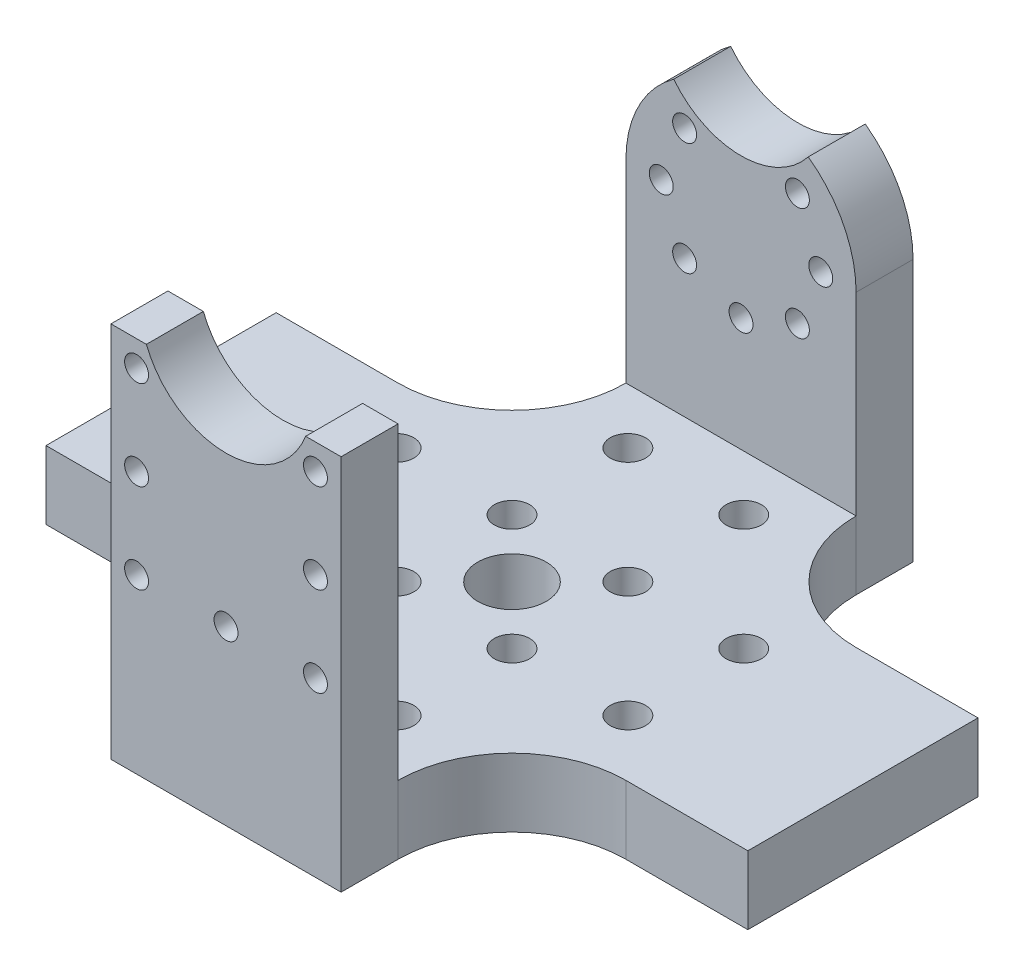
SolidWorks part; units mm, degrees
ref_plane "Front Plane" through (0, 0, 0) normal (0, 0, 1) x (1, 0, 0)
ref_plane "Top Plane" through (0, 0, 0) normal (0, 1, 0) x (1, 0, 0)
ref_plane "Right Plane" through (0, 0, 0) normal (1, 0, 0) x (0, 0, -1)
sketch "Sketch1" plane through (0, 0, 0) normal (0, 0, 1) x (1, 0, 0)
  line L0 (0, 0) -> (0, -20) construction
  line L1 (-10.1, 0) -> (-10.1, -20)
  line L2 (10.1, 0) -> (10.1, -20)
  line L3 (-10.1, -20) -> (10.1, -20)
  arc A0 (10.1, 0) -> (-10.1, 0) centre (0, 0) ccw
  dimension "D1" = 20.2
  dimension "D2" = 20
extrude "Boss-Extrude1" add sketch "Sketch1" along normal blind 50.2
sketch "Sketch2" plane through (-10.1, 0, 0) normal (-1, 0, 0) x (0, 0, 1)
  line L0 (50.2, -10) -> (45.2, -10) construction
  line L1 (50.2, 0) -> (50.2, -20) construction
  line L2 (0, -10) -> (5, -10) construction
  line L3 (0, 0) -> (0, -20) construction
  line L4 (25.1, -20) -> (25.1, -17) construction
  line L5 (50.2, -20) -> (0, -20) construction
  line L6 (5, -10) -> (5, -17)
  line L7 (5, -17) -> (45.2, -17)
  line L8 (45.2, -17) -> (45.2, -10)
  line L9 (45.2, -10) -> (45.2, 11.8668)
  line L10 (45.2, 11.8668) -> (5, 11.8668)
  line L11 (5, 11.8668) -> (5, -10)
  dimension "D1" = 5
  dimension "D2" = 5
  dimension "D3" = 3
extrude "Cut-Extrude2" cut sketch "Sketch2" against normal blind 44.2
sketch "Sketch3" plane through (0, 0, 50.2) normal (0, 0, 1) x (1, 0, 0)
  line L0 (0, 10.1) -> (-10.1, 10.1) construction
  line L1 (-10.1, 10.1) -> (-10.1, 0) construction
  line L2 (0, 10.1) -> (10.1, 10.1) construction
  line L3 (10.1, 10.1) -> (10.1, 0) construction
  line L4 (-10.1, 0) -> (-10.1, 10.1)
  line L5 (-10.1, 10.1) -> (10.1, 10.1)
  line L6 (10.1, 10.1) -> (10.1, 0)
  line L7 (10.1, 0) -> (-10.1, 0)
  arc A0 (10.1, 0) -> (-10.1, 0) centre (0, 0) ccw construction
extrude "Boss-Extrude2" add sketch "Sketch3" against normal blind 5
sketch "Sketch4" plane through (0, 0, 50.2) normal (0, 0, 1) x (1, 0, 0)
  line L0 (0, 0) -> (-10.1, 0) construction
  line L1 (-10.1, 10.1) -> (-10.1, -20) construction
  line L2 (-10.1, 0) -> (10.1, 0) construction
  line L3 (-10.1, 10.1) -> (-10.1, -9.9) construction
  line L4 (-10.1, -9.9) -> (10.1, -9.9) construction
  line L5 (10.1, -20) -> (10.1, 10.1) construction
  line L6 (10.1, -9.9) -> (10.1, 10.1) construction
  line L7 (10.1, 10.1) -> (-10.1, 10.1) construction
  line L8 (0, 10.1) -> (0, -9.9) construction
  line L9 (10.1, -9.9) -> (10.1, 10.1) construction
  line L10 (10.1, 10.1) -> (-10.1, -9.9) construction
  line L11 (-6.8, 7.85) -> (6.8, 7.85) construction
  line L12 (-6.8, -7.85) -> (6.8, -7.85) construction
  circle A2 centre (-7.85, 7.85) radius 1.05
  circle A3 centre (7.85, 7.85) radius 1.05
  circle A4 centre (-7.85, -7.85) radius 1.05
  circle A5 centre (7.85, -7.85) radius 1.05
  circle A6 centre (0, 7.85) radius 1.05
  circle A7 centre (0, -7.85) radius 1.05
  circle A8 centre (-7.85, 0) radius 1.05
  circle A9 centre (7.85, 0) radius 1.05
  dimension "D1" = 2.1
  dimension "D2" = 20
  dimension "D4" = 2.25
  dimension "D5" = 2.1
  dimension "D6" = 2.1
  dimension "D7" = 2.1
  dimension "D8" = 2.1
  dimension "D9" = 2.25
  dimension "D10" = 2.25
  dimension "D3" = 2.25
extrude "Cut-Extrude3" cut sketch "Sketch4" against normal mid plane 22
sketch "Sketch5" plane through (0, 0, 50.2) normal (0, 0, 1) x (1, 0, 0)
  line L0 (0, -4) -> (0, 20.32) construction
  circle A0 centre (0, 0) radius 4
  circle A1 centre (0, 12.82) radius 7.5
  dimension "D1" = 8
  dimension "D2" = 15
  dimension "D3" = 24.32
extrude "Cut-Extrude4" cut sketch "Sketch5" against normal mid plane 22
sketch "Sketch6" plane through (0, 0, 50.2) normal (0, 0, 1) x (1, 0, 0)
  circle A0 centre (0, 0) radius 4
  dimension "D1" = 8
extrude "Boss-Extrude3" add sketch "Sketch6" against normal blind 5
sketch "Sketch7" plane through (0, 0, 0) normal (0, 0, -1) x (-1, 0, 0)
  line L0 (0, 4) -> (0, 6) construction
  line L1 (0, 6) -> (0, 7) construction
  circle A0 centre (0, 0) radius 4
  circle A1 centre (0, 7) radius 1.05
  circle A2 centre (-4.9497, 4.9497) radius 1.05
  circle A3 centre (-7, 0) radius 1.05
  circle A4 centre (-4.9497, -4.9497) radius 1.05
  circle A5 centre (0, -7) radius 1.05
  circle A6 centre (4.9497, -4.9497) radius 1.05
  circle A7 centre (7, 0) radius 1.05
  circle A8 centre (4.9497, 4.9497) radius 1.05
  point P24 (0, 0)
  dimension "D1" = 8
  dimension "D4" = 2.1
  dimension "D2" = 2
  dimension "D3" = 1
  dimension "D5" = 8
extrude "Cut-Extrude5" cut sketch "Sketch7" against normal mid plane 32
sketch "Sketch8" plane through (0, 0, 0) normal (0, 0, -1) x (-1, 0, 0)
  line L0 (0, 20.32) -> (0, -4) construction
  circle A1 centre (0, 12.82) radius 7.5
  circle A2 centre (0, 0) radius 4 construction
  dimension "D1" = 15
  dimension "D2" = 24.32
extrude "Cut-Extrude6" cut sketch "Sketch8" against normal mid plane 22
sketch "Sketch9" plane through (0, 0, 0) normal (0, 0, -1) x (-1, 0, 0)
  circle A0 centre (0, 0) radius 4
  dimension "D1" = 8
extrude "Boss-Extrude4" add sketch "Sketch9" against normal blind 5
ref_plane "Plane1" through (0, -20, 0) normal (0, -1, 0) x (-1, 0, 0)
sketch "Sketch11" plane through (0, -20, 0) normal (0, -1, 0) x (-1, 0, 0)
  line L1 (-10.1, 0) -> (10.1, 0)
  line L2 (-10.1, 0) -> (-10.1, -50.2)
  line L3 (-10.1, -50.2) -> (10.1, -50.2)
  line L4 (10.1, 0) -> (10.1, -50.2)
extrude "Boss-Extrude5" add sketch "Sketch11" along normal blind 3
ref_plane "Plane2" through (0, -17, 0) normal (0, 1, 0) x (1, 0, 0)
sketch "Sketch12" plane through (0, -17, 0) normal (0, 1, 0) x (1, 0, 0)
  line L0 (-10.1, -25.1) -> (10.1, -25.1) construction
  line L1 (-10.1, -5) -> (-10.1, -45.2) construction
  line L2 (10.1, -5) -> (10.1, -45.2) construction
  line L3 (0, -5) -> (0, -45.2) construction
  line L4 (10.1, -5) -> (-10.1, -5) construction
  line L5 (10.1, -45.2) -> (-10.1, -45.2) construction
  line L6 (0, -25.1) -> (-5.0841, -20.0159) construction
  line L7 (-5.0841, -20.0159) -> (-5.0841, -25.1) construction
  circle A0 centre (0, -25.1) radius 3
  circle A1 centre (-5.0841, -20.0159) radius 1.55
  circle A5 centre (5.0841, -20.0159) radius 1.55
  circle A6 centre (5.0841, -30.1841) radius 1.55
  circle A7 centre (-5.0841, -30.1841) radius 1.55
  point P25 (-0.3874, -24.4228)
  point P26 (0, -25.1)
  dimension "D1" = 6
  dimension "D2" = 3.1
  dimension "D3" = 90
  dimension "D4" = 45
  dimension "D6" = 4
  dimension "D5" = 7.19
extrude "Cut-Extrude8" cut sketch "Sketch12" against normal blind 23
ref_plane "Plane3" through (0, -23, 0) normal (0, -1, 0) x (-1, 0, 0)
sketch "Sketch13" plane through (0, -23, 0) normal (0, -1, 0) x (-1, 0, 0)
  line L0 (10.1, 0) -> (10.1, -15) construction
  line L1 (10.1, -50.2) -> (10.1, 0) construction
  line L2 (10.1, -50.2) -> (10.1, -35.2) construction
  line L3 (10.1, -15) -> (10.1, -35.2)
  line L4 (10.1, -35.2) -> (30.8, -35.2)
  line L5 (30.8, -35.2) -> (30.8, -15)
  line L6 (30.8, -15) -> (10.1, -15)
  line L7 (0, 0) -> (0, -50.2) construction
  line L8 (-10.1, -50.2) -> (10.1, -50.2) construction
  line L9 (-30.8, -35.2) -> (-30.8, -15)
  line L10 (-10.1, -35.2) -> (-30.8, -35.2)
  line L11 (-10.1, -15) -> (-10.1, -35.2)
  line L12 (-30.8, -15) -> (-10.1, -15)
  dimension "D1" = 15
  dimension "D2" = 15
  dimension "D3" = 20.7
extrude "Boss-Extrude6" add sketch "Sketch13" against normal blind 6
ref_plane "Plane4" through (0, -23, 0) normal (0, -1, 0) x (-1, 0, 0)
sketch "Sketch14" plane through (0, -23, 0) normal (0, -1, 0) x (1, 0, 0)
  line L0 (-5.0841, 20.0159) -> (-15.2541, 20.0159) construction
  line L1 (0, 25.1) -> (-30.8, 25.1) construction
  line L2 (-30.8, 35.2) -> (-30.8, 15) construction
  line L3 (0, 35.7754) -> (0, 0) construction
  circle A0 centre (-15.2541, 20.0159) radius 1.55
  circle A1 centre (-15.2541, 30.1841) radius 1.55
  circle A2 centre (15.2541, 30.1841) radius 1.55
  circle A3 centre (15.2541, 20.0159) radius 1.55
  dimension "D2" = 3.1
  dimension "D1" = 10.17
extrude "Cut-Extrude9" cut sketch "Sketch14" against normal blind 6
ref_plane "Plane5" through (0, -23, 0) normal (0, -1, 0) x (-1, 0, 0)
sketch "Sketch15" plane through (0, -23, 0) normal (0, -1, 0) x (-1, 0, 0)
  line L0 (-5.0841, -20.0159) -> (-5.0841, -9.8459) construction
  line L1 (0, -25.1) -> (0, 0) construction
  line L2 (-15.044, -25.1) -> (30.8, -25.1) construction
  line L3 (30.8, -35.2) -> (30.8, -15) construction
  circle A0 centre (-5.0841, -9.8459) radius 1.55
  circle A1 centre (5.0841, -9.8459) radius 1.55
  circle A2 centre (-5.0841, -40.3541) radius 1.55
  circle A3 centre (5.0841, -40.3541) radius 1.55
  dimension "D2" = 3.1
  dimension "D1" = 10.17
extrude "Cut-Extrude10" cut sketch "Sketch15" against normal blind 6
ref_plane "Plane6" through (-10.1, 0, 0) normal (-1, 0, 0) x (0, 0, 1)
fillet "Fillet1" radius 10 1 edges at (-10.1, -20, 35.2)
ref_plane "Plane7" through (-10.1, 0, 0) normal (-1, 0, 0) x (0, 0, 1)
fillet "Fillet2" radius 10 2 edges at (-10.1, -17, 10) (-10.1, -20, 15)
ref_plane "Plane8" through (10.1, 0, 0) normal (1, 0, 0) x (0, 0, -1)
fillet "Fillet3" radius 10 2 edges at (10.1, -20, 35.2) (10.1, -20, 15)
